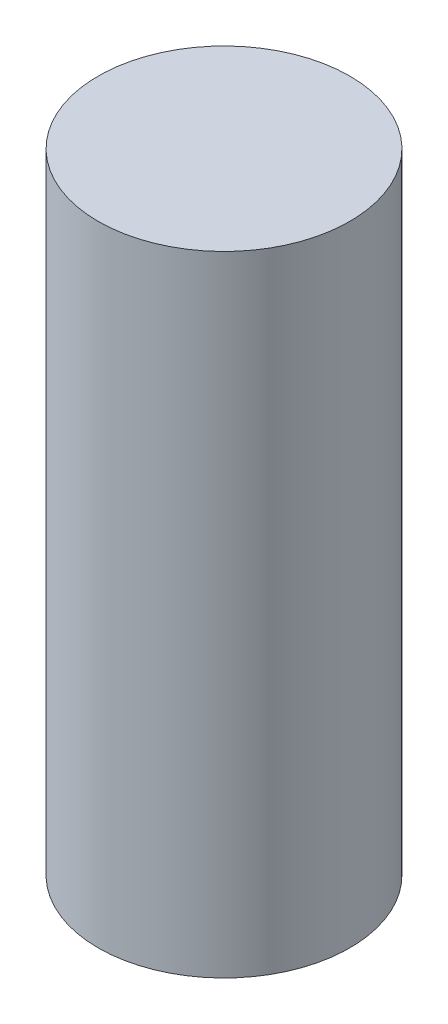
SolidWorks part; units mm, degrees
ref_plane "Front Plane" through (0, 0, 0) normal (0, 0, 1) x (1, 0, 0)
ref_plane "Top Plane" through (0, 0, 0) normal (0, 1, 0) x (1, 0, 0)
ref_plane "Right Plane" through (0, 0, 0) normal (1, 0, 0) x (0, 0, -1)
sketch "Sketch1" plane through (0, 0, 0) normal (0, 1, 0) x (1, 0, 0)
  circle A0 centre (0, 0) radius 4
  dimension "D1" = 8
extrude "Boss-Extrude1" add sketch "Sketch1" along normal blind 20
